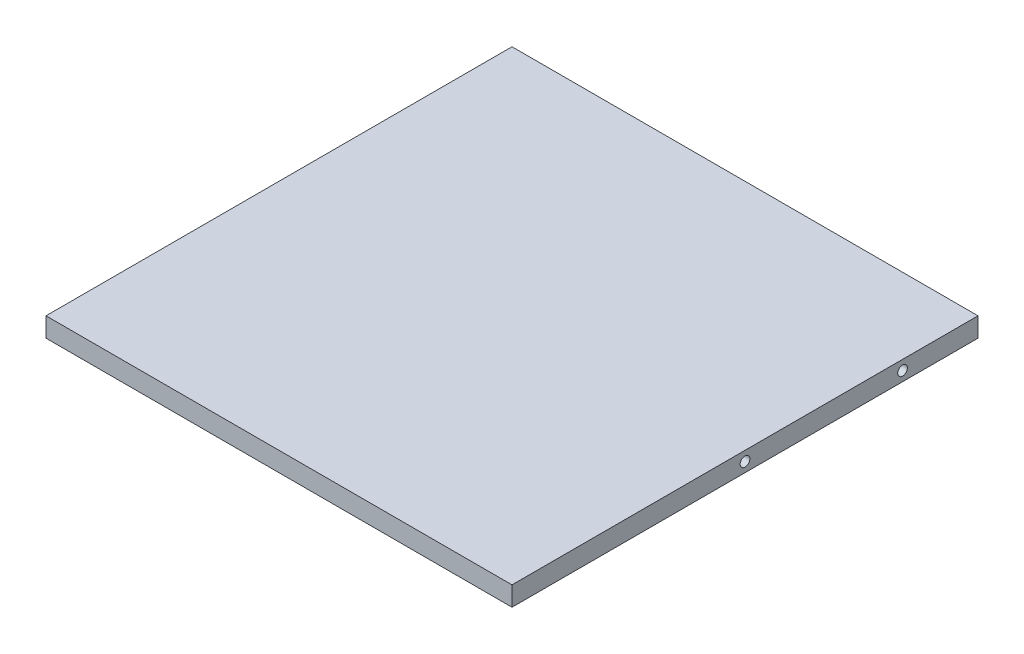
SolidWorks part; units mm, degrees
ref_plane "Front Plane" through (0, 0, 0) normal (0, 0, 1) x (1, 0, 0)
ref_plane "Top Plane" through (0, 0, 0) normal (0, 1, 0) x (1, 0, 0)
ref_plane "Right Plane" through (0, 0, 0) normal (1, 0, 0) x (0, 0, -1)
sketch "Sketch2" plane through (0, 0, 0) normal (0, 1, 0) x (1, 0, 0)
  line L1 (-250.8402, 154.9522) -> (53.9598, 154.9522)
  line L2 (-250.8402, 154.9522) -> (-250.8402, -149.8478)
  line L3 (-250.8402, -149.8478) -> (53.9598, -149.8478)
  line L4 (53.9598, 154.9522) -> (53.9598, -149.8478)
  dimension "D1" = 304.8
  dimension "D2" = 304.8
extrude "Boss-Extrude1" add sketch "Sketch2" along normal blind 12.7
sketch "Sketch3" plane through (53.9598, 0, 0) normal (1, 0, 0) x (0, 0, -1)
  circle A0 centre (2.5522, 6.35) radius 3.175
  dimension "D1" = 6.35
extrude "Cut-Extrude1" cut sketch "Sketch3" against normal through all
sketch "Sketch4" plane through (-250.8402, 0, 0) normal (-1, 0, 0) x (0, 0, 1)
  circle A0 centre (-105.6005, 6.35) radius 3.175
  point P2 (-105.6005, 6.35)
extrude "Cut-Extrude2" cut sketch "Sketch4" against normal through all
